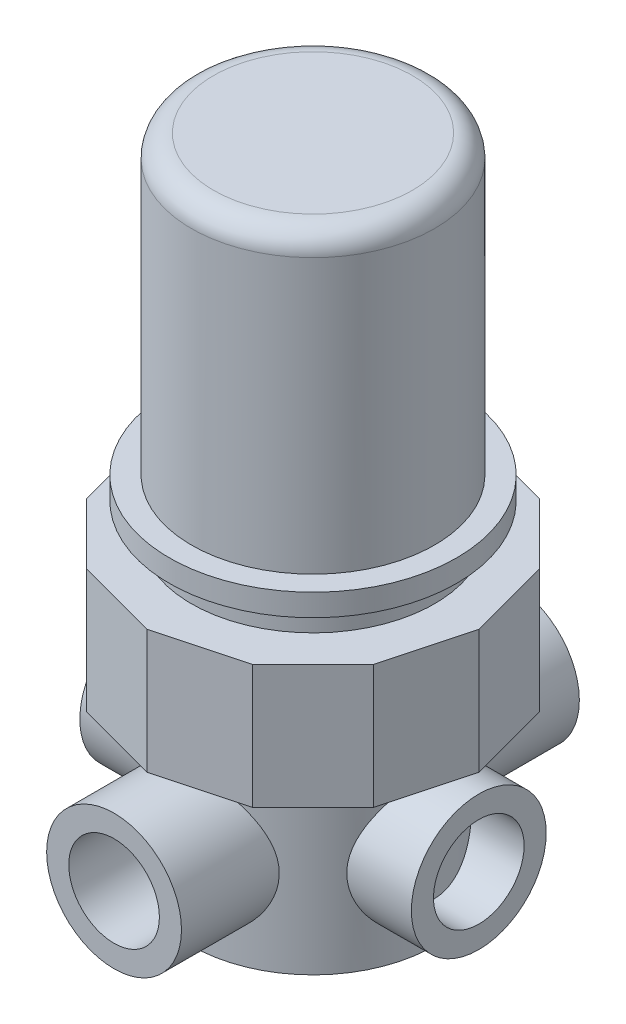
SolidWorks part; units mm, degrees
ref_plane "Front Plane" through (0, 0, 0) normal (0, 0, 1) x (1, 0, 0)
ref_plane "Top Plane" through (0, 0, 0) normal (0, 1, 0) x (1, 0, 0)
ref_plane "Right Plane" through (0, 0, 0) normal (1, 0, 0) x (0, 0, -1)
sketch "Sketch1" plane through (0, 0, 0) normal (0, 0, 1) x (1, 0, 0)
  line L0 (0, 73.914) -> (0, 0) construction
  line L1 (0, 73.914) -> (13.97, 73.914)
  line L2 (13.97, 73.914) -> (13.97, 39.878)
  line L3 (13.97, 39.878) -> (16.51, 39.878)
  line L4 (16.51, 39.878) -> (16.51, 37.338)
  line L5 (16.51, 37.338) -> (13.97, 37.338)
  line L6 (13.97, 37.338) -> (13.97, 34.036)
  line L7 (13.97, 34.036) -> (19.05, 34.036)
  line L8 (19.05, 34.036) -> (19.05, 19.812)
  line L9 (19.05, 19.812) -> (13.97, 19.812)
  line L10 (13.97, 19.812) -> (13.97, 0)
  line L11 (13.97, 0) -> (0, 0)
  line L12 (0, 73.914) -> (0, 0)
  dimension "D1" = 27.94
  dimension "D2" = 38.1
  dimension "D3" = 2.54
  dimension "D4" = 3.302
  dimension "D5" = 19.812
  dimension "D6" = 14.224
  dimension "D7" = 73.914
revolve "Revolve1" add sketch "Sketch1" angle 360 about L0
sketch "Sketch2" plane through (0, 34.036, 0) normal (0, 1, 0) x (1, 0, 0)
  line L1 (0, 19.05) -> (-9.525, 16.4978)
  line L2 (-9.525, 16.4978) -> (-16.4978, 9.525)
  line L3 (-16.4978, 9.525) -> (-19.05, 0)
  line L4 (-19.05, 0) -> (-16.4978, -9.525)
  line L5 (-16.4978, -9.525) -> (-9.525, -16.4978)
  line L6 (-9.525, -16.4978) -> (0, -19.05)
  line L7 (0, -19.05) -> (9.525, -16.4978)
  line L8 (9.525, -16.4978) -> (16.4978, -9.525)
  line L9 (16.4978, -9.525) -> (19.05, 0)
  line L10 (19.05, 0) -> (16.4978, 9.525)
  line L11 (16.4978, 9.525) -> (9.525, 16.4978)
  line L12 (9.525, 16.4978) -> (0, 19.05)
  circle A0 centre (0, 0) radius 18.4009 construction
  circle A1 centre (0, 0) radius 19.05 construction
  circle A3 centre (0, 0) radius 19.05
  circle M2 centre (0, 0) radius 19.05
extrude "Cut-Extrude1" cut sketch "Sketch2" against normal up to next contours L2 M2 | L3 M2 | L4 M2 | L5 M2 | L6 M2 | L7 M2 | L8 M2 | L9 M2 | L10 M2 | L11 M2 | L12 M2 | L1 M2 | A3
ref_plane "Plane1" through (0, 0, 13.97) normal (0, 0, 1) x (1, 0, 0)
sketch "Sketch3" plane through (0, 0, 13.97) normal (0, 0, 1) x (1, 0, 0)
  line L0 (0, 19.812) -> (0, 0) construction
  circle A0 centre (0, 9.906) radius 5.207
  circle A1 centre (0, 9.906) radius 7.747
  dimension "D1" = 10.414
  dimension "D2" = 2.54
extrude "Boss-Extrude1" add sketch "Sketch3" along normal blind 8.89 and the other way up to next (8.89 mm away)
pattern_circular "CirPattern1" count 4 over 360 about axis through (0, 0, 0) along (0, 1, 0) of "Boss-Extrude1"
sketch "Sketch4" plane through (22.86, 0, 0) normal (1, 0, 0) x (0, 0, -1)
  circle A1 centre (0, 9.906) radius 7.747
  circle A2 centre (0, 9.906) radius 7.747
  dimension "D1" = 0
extrude "Cut-Extrude2" cut sketch "Sketch4" against normal blind 3.81
mirror "Mirror2" about plane through (0, 0, 0) normal (1, 0, 0) of "Cut-Extrude2"
fillet "Fillet1" radius 2.54 1 edges at (-13.97, 73.914, 0)
